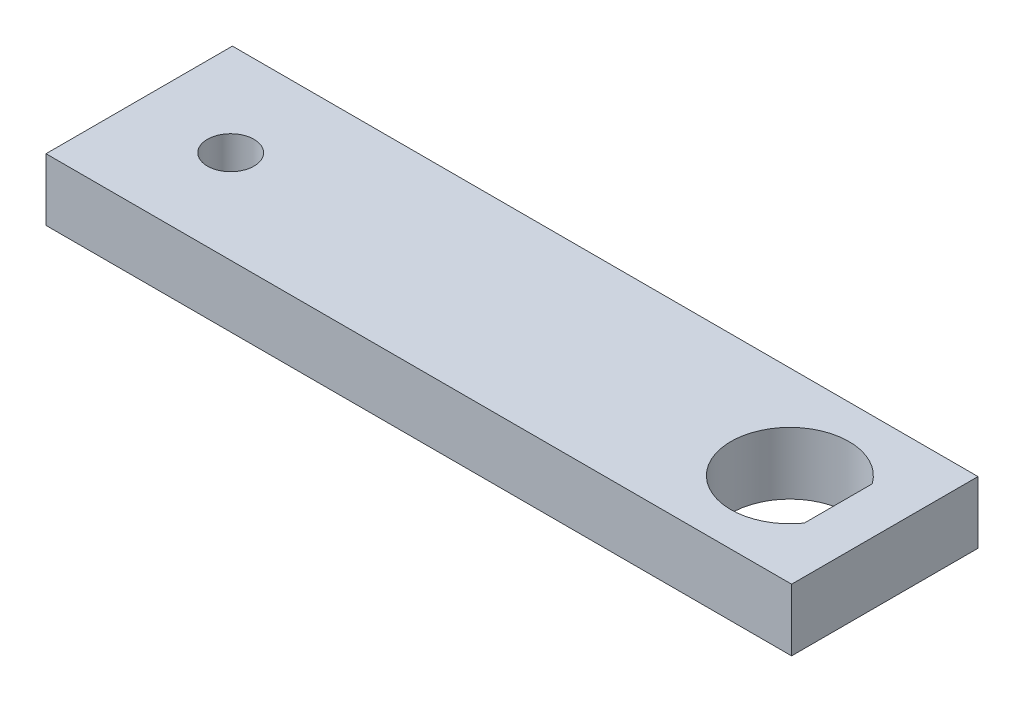
SolidWorks part; units mm, degrees
ref_plane "Ön Düzlem" through (0, 0, 0) normal (0, 0, 1) x (1, 0, 0)
ref_plane "Üst Düzlem" through (0, 0, 0) normal (0, 1, 0) x (1, 0, 0)
ref_plane "Sağ Düzlem" through (0, 0, 0) normal (1, 0, 0) x (0, 0, -1)
sketch "Çizim1" plane through (0, 0, 0) normal (0, 1, 0) x (1, 0, 0)
  line L0 (30.3249, 10.1821) -> (30.3249, 3.2488)
  line L1 (-41.1151, 16.2405) -> (35.0849, 16.2405)
  line L2 (-41.1151, 16.2405) -> (-41.1151, -2.8095)
  line L3 (-41.1151, -2.8095) -> (35.0849, -2.8095)
  line L4 (35.0849, 16.2405) -> (35.0849, -2.8095)
  circle A0 centre (-31.7651, 6.7155) radius 2.38
  arc A1 (30.3249, 10.1821) -> (30.3249, 3.2488) centre (25.3849, 6.7155) ccw
  point P8 (-41.1151, 6.7155)
  point P9 (35.0849, 6.7155)
  dimension "D3" = 12.07
  dimension "D4" = 4.76
  dimension "D1" = 19.05
  dimension "D2" = 76.2
  dimension "D5" = 9.35
  dimension "D6" = 9.7
  dimension "D7" = 4.76
extrude "Yükseklik-Ekstrüzyon1" add sketch "Çizim1" along normal blind 6.35
